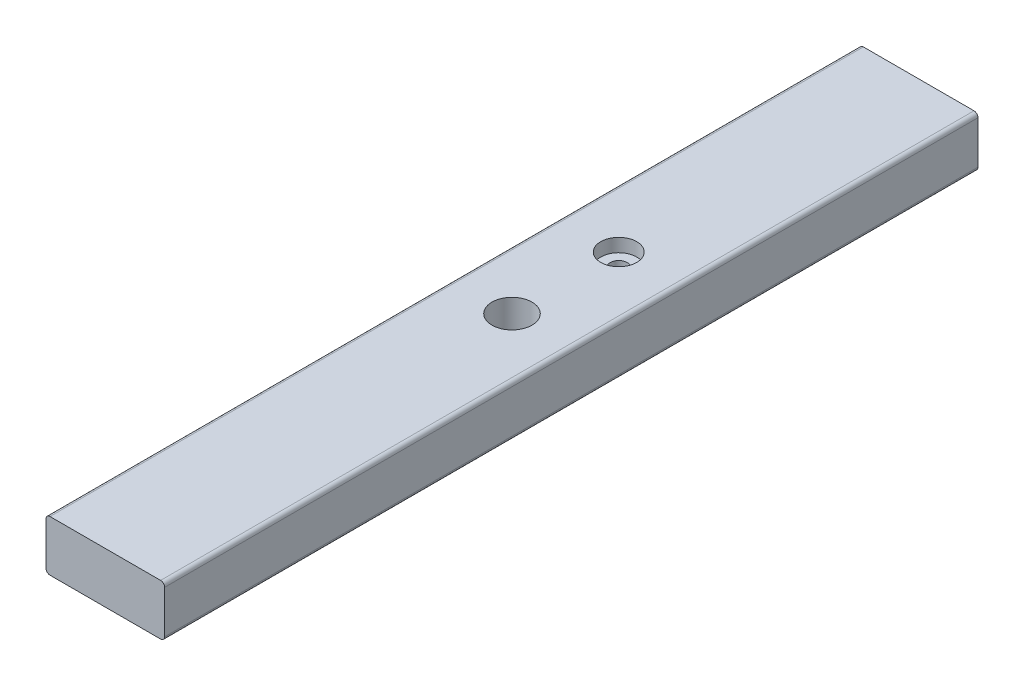
SolidWorks part; units mm, degrees
material "Pine"
ref_plane "Front Plane" through (0, 0, 0) normal (0, 0, 1) x (1, 0, 0)
ref_plane "Top Plane" through (0, 0, 0) normal (0, 1, 0) x (1, 0, 0)
ref_plane "Right Plane" through (0, 0, 0) normal (1, 0, 0) x (0, 0, -1)
sketch "Sketch1" plane through (0, 0, 0) normal (0, 0, 1) x (1, 0, 0)
  line L1 (41.45, -19.05) -> (-41.45, -19.05)
  line L2 (44.45, -16.05) -> (44.45, 16.05)
  line L3 (41.45, 19.05) -> (-41.45, 19.05)
  line L4 (-44.45, -16.05) -> (-44.45, 16.05)
  line L5 (44.45, -19.05) -> (-44.45, 19.05) construction
  line L6 (44.45, 19.05) -> (-44.45, -19.05) construction
  arc A0 (-41.45, -19.05) -> (-44.45, -16.05) centre (-41.45, -16.05) cw
  arc A1 (-41.45, 19.05) -> (-44.45, 16.05) centre (-41.45, 16.05) ccw
  arc A2 (44.45, 16.05) -> (41.45, 19.05) centre (41.45, 16.05) ccw
  arc A3 (41.45, -19.05) -> (44.45, -16.05) centre (41.45, -16.05) ccw
  point P0 (0, 0)
  dimension "D3" = 3
  dimension "D1" = 88.9
  dimension "D2" = 38.1
extrude "Boss-Extrude1" add sketch "Sketch1" along normal blind 609.6
sketch "Sketch2" plane through (0, 19.05, 0) normal (0, 1, 0) x (1, 0, 0)
  line L0 (-41.45, -609.6) -> (-41.45, 0) construction
  circle A0 centre (0, -304.8) radius 15
  circle A1 centre (0, -224.8) radius 6.35
  point P10 (-41.45, -304.8)
  dimension "D1" = 30
  dimension "D2" = 12.7
  dimension "D3" = 80
extrude "Cut-Extrude1" cut sketch "Sketch2" against normal through all
sketch "Sketch3" plane through (0, 19.05, 0) normal (0, 1, 0) x (1, 0, 0)
  circle A0 centre (0, -224.8) radius 13.5001
  dimension "D1" = 27.0002
extrude "Cut-Extrude2" cut sketch "Sketch3" against normal blind 10
mirror "Mirror1" about plane through (0, 0, 0) normal (0, 1, 0) of "Cut-Extrude2"
equation "\"ChainSeperation\"= 80"
